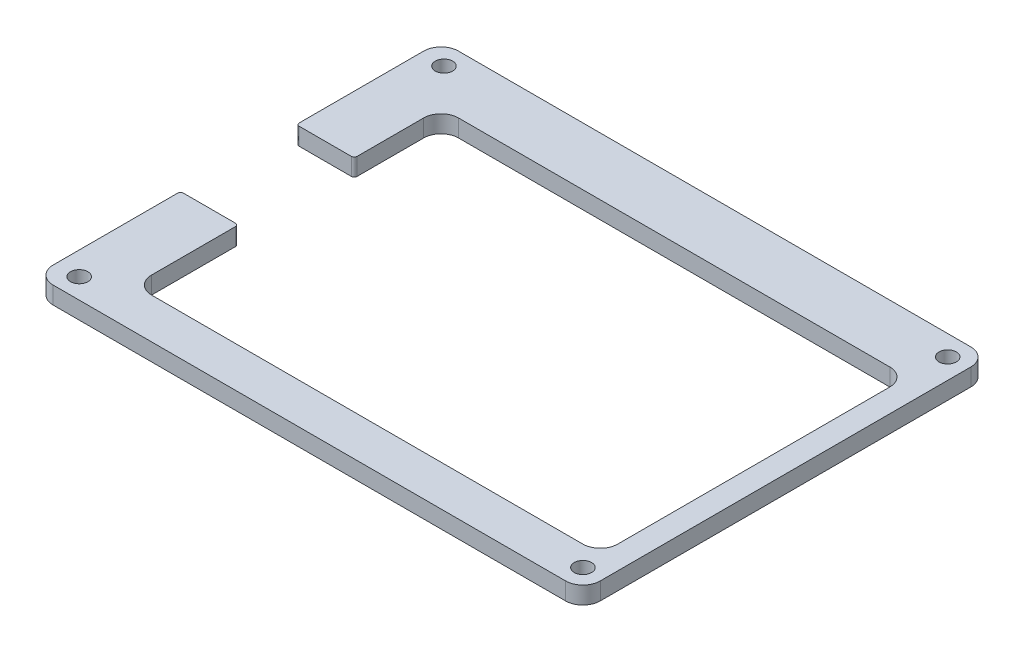
SolidWorks part; units mm, degrees
material "ABS"
ref_plane "Front Plane" through (0, 0, 0) normal (0, 0, 1) x (1, 0, 0)
ref_plane "Top Plane" through (0, 0, 0) normal (0, 1, 0) x (1, 0, 0)
ref_plane "Right Plane" through (0, 0, 0) normal (1, 0, 0) x (0, 0, -1)
sketch "Sketch1" plane through (0, 0, 0) normal (0, 1, 0) x (1, 0, 0)
  line L1 (-47.25, 35) -> (47.25, 35)
  line L2 (-47.25, 35) -> (-47.25, -35)
  line L3 (-47.25, -35) -> (47.25, -35)
  line L4 (47.25, 35) -> (47.25, -35)
  line L5 (-47.25, 35) -> (47.25, -35) construction
  line L6 (-47.25, -35) -> (47.25, 35) construction
  point P0 (0, 0)
  dimension "D1" = 70
  dimension "D2" = 94.5
extrude "Boss-Extrude1" add sketch "Sketch1" along normal blind 3
sketch "Sketch3" plane through (0, 3, 0) normal (0, 1, 0) x (1, 0, 0)
  line L0 (47.25, -35) -> (47.25, 35) construction
  line L2 (47.25, 35) -> (-47.25, 35) construction
  circle A0 centre (43.75, 31.5) radius 1.5
  circle A1 centre (-43.25, 31.5) radius 1.5
  circle A2 centre (-43.25, -31.5) radius 1.5
  circle A3 centre (43.75, -31.5) radius 1.5
  dimension "D1" = 3
  dimension "D2" = 3.5
  dimension "D3" = 3.5
  dimension "D4" = 2
  dimension "D5" = 87
  dimension "D6" = 63
  dimension "D7" = 2
extrude "Cut-Extrude2" cut sketch "Sketch3" against normal through all
fillet "Fillet2" radius 3 4 edges at (-47.25, 1.5, 35) (-47.25, 1.5, -35) (47.25, 1.5, -35) (47.25, 1.5, 35)
sketch "Sketch5" plane through (0, 3, 0) normal (0, 1, 0) x (1, 0, 0)
  line L0 (-37.25, 25) -> (43.25, 25)
  line L3 (-37.25, -28) -> (-37.25, 25)
  line L15 (-30, -28) -> (43.25, -28)
  line L17 (44.25, 35) -> (-44.25, 35) construction
  line L18 (-47.25, 32) -> (-47.25, -32) construction
  line L27 (43.25, 25) -> (43.25, -28)
  line L28 (-30, -28) -> (-37.25, -28)
  line L29 (47.25, -32) -> (47.25, 32) construction
  line L30 (-37.25, 10) -> (-47.25, 10)
  line L31 (-47.25, 10) -> (-47.25, -10)
  line L32 (-47.25, -10) -> (-37.25, -10)
  line L33 (-44.25, -35) -> (44.25, -35) construction
  line M17 (-47.25, 32) -> (-47.25, -32)
  dimension "D1" = 10
  dimension "D2" = 10
  dimension "D3" = 4
  dimension "D4" = 7
  dimension "D5" = 25
  dimension "D7" = 20
extrude "Cut-Extrude3" cut sketch "Sketch5" against normal through all contours L28 L15 L27 L0 L3 | L32 L3 L30 M17
fillet "Fillet3" radius 3 4 edges at (-37.25, 1.5, -25) (-37.25, 1.5, 28) (43.25, 1.5, 28) (43.25, 1.5, -25)
fillet "Fillet4" radius 0.5 4 edges at (-47.25, 1.5, 10) (-37.25, 1.5, 10) (-37.25, 1.5, -10) (-47.25, 1.5, -10)
